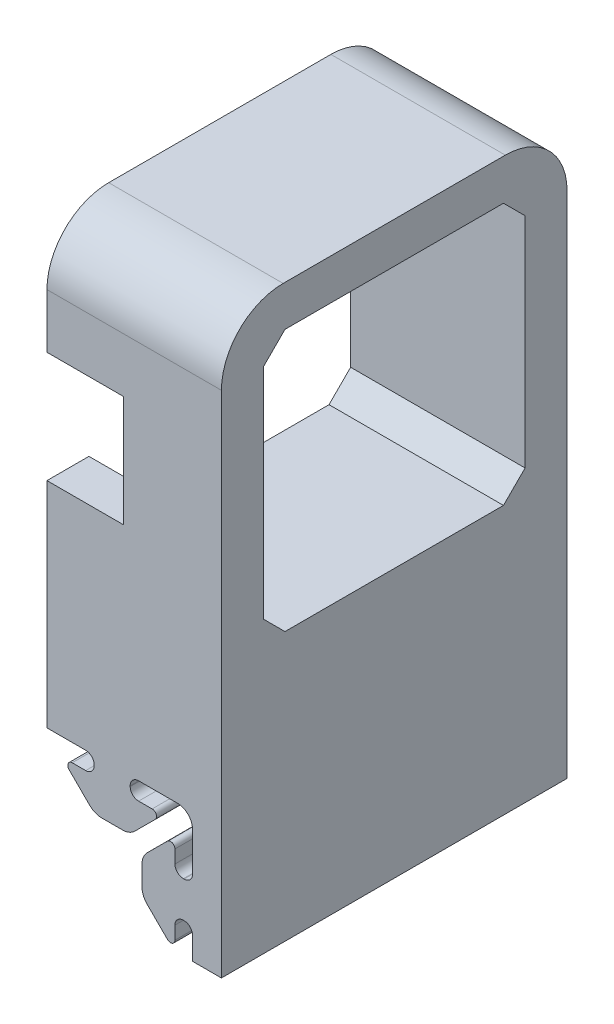
SolidWorks part; units mm, degrees
ref_plane "Front Plane" through (0, 0, 0) normal (0, 0, 1) x (1, 0, 0)
ref_plane "Top Plane" through (0, 0, 0) normal (0, 1, 0) x (1, 0, 0)
ref_plane "Right Plane" through (0, 0, 0) normal (1, 0, 0) x (0, 0, -1)
sketch "Sketch1" plane through (0, 0, 0) normal (0, 0, 1) x (1, 0, 0)
  line L0 (13.02, -7.9417) -> (17.7, -7.9417)
  line L1 (-10.5664, 13.02) -> (-10.5664, 84.52)
  line L2 (-10.5664, 84.52) -> (17.7, 84.52)
  line L3 (17.7, -7.9417) -> (17.7, 84.52)
  line L10 (12.7, -6.3331) -> (12.7, -7.9417) construction
  line L11 (13.02, -5.3171) -> (13.02, -4.2875)
  line L12 (11.651, -2.9185) -> (11.5392, -2.9185)
  line L13 (10.1702, -4.2875) -> (10.1702, -6.4021)
  line L14 (8.9631, -6.9029) -> (5.667, -3.6143)
  line L15 (4.8285, -1.5932) -> (4.8285, 1.5932)
  line L16 (5.667, 3.6143) -> (8.9631, 6.9029)
  line L17 (10.1702, 6.4021) -> (10.1702, 4.2875)
  line L18 (11.5392, 2.9185) -> (11.651, 2.9185)
  line L19 (13.02, 10.5773) -> (13.02, 4.2875)
  line L20 (6.3329, 13.02) -> (10.5626, 13.0198)
  line L22 (6.3329, 13.02) -> (4.2875, 13.02)
  line L23 (2.9185, 11.651) -> (2.9185, 11.5392)
  line L24 (4.2875, 10.1702) -> (6.4768, 10.1702)
  line L25 (6.981, 8.9509) -> (3.6723, 5.6497)
  line L26 (1.6558, 4.8158) -> (-1.6558, 4.8158)
  line L27 (-3.6723, 5.6497) -> (-6.981, 8.9509)
  line L28 (-6.4768, 10.1702) -> (-4.2875, 10.1702)
  line L29 (-2.9185, 11.5392) -> (-2.9185, 11.651)
  line L30 (-4.2875, 13.02) -> (-5.3171, 13.02)
  line L31 (-5.3171, 13.02) -> (-10.5664, 13.02)
  line L32 (13.02, -5.3171) -> (13.02, -7.9417)
  line L33 (13.02, -6.3331) -> (13.02, -7.9417) construction
  line L34 (13.02, 4.2875) -> (13.02, 5.3171) construction
  line L37 (5.3171, 13.02) -> (4.2875, 13.02) construction
  line L38 (-6.3331, 13.02) -> (-9.5504, 13.02) construction
  line L96 (12.7, -5.3171) -> (12.7, -4.2875) construction
  line L97 (11.651, -3.2385) -> (11.5392, -3.2385) construction
  line L98 (10.4902, -4.2875) -> (10.4902, -6.4021) construction
  line L99 (8.7371, -7.1294) -> (5.441, -3.8408) construction
  line L100 (4.5085, -1.5932) -> (4.5085, 1.5932) construction
  line L101 (5.441, 3.8408) -> (8.7371, 7.1294) construction
  line L102 (10.4902, 6.4021) -> (10.4902, 4.2875) construction
  line L103 (11.5392, 3.2385) -> (11.651, 3.2385) construction
  line L104 (12.7, 4.2875) -> (12.7, 5.3171) construction
  line L105 (12.7, 6.3331) -> (12.7, 9.5504) construction
  line L106 (9.5504, 12.7) -> (6.3331, 12.7) construction
  line L107 (5.3171, 12.7) -> (4.2875, 12.7) construction
  line L108 (3.2385, 11.651) -> (3.2385, 11.5392) construction
  line L109 (4.2875, 10.4902) -> (6.4768, 10.4902) construction
  line L110 (7.207, 8.7244) -> (3.8983, 5.4232) construction
  line L111 (1.6558, 4.4958) -> (-1.6558, 4.4958) construction
  line L112 (-3.8983, 5.4232) -> (-7.207, 8.7244) construction
  line L113 (-6.4768, 10.4902) -> (-4.2875, 10.4902) construction
  line L114 (-3.2385, 11.5392) -> (-3.2385, 11.651) construction
  line L115 (-4.2875, 12.7) -> (-5.3171, 12.7) construction
  line L116 (-6.3331, 12.7) -> (-9.5504, 12.7) construction
  arc A0 (13.02, -4.2875) -> (11.651, -2.9185) centre (11.651, -4.2875) ccw
  arc A1 (11.5392, -2.9185) -> (10.1702, -4.2875) centre (11.5392, -4.2875) ccw
  arc A2 (8.9631, -6.9029) -> (10.1702, -6.4021) centre (9.4628, -6.4021) ccw
  arc A3 (4.8285, -1.5932) -> (5.667, -3.6143) centre (7.6835, -1.5932) ccw
  arc A4 (5.667, 3.6143) -> (4.8285, 1.5932) centre (7.6835, 1.5932) ccw
  arc A5 (10.1702, 6.4021) -> (8.9631, 6.9029) centre (9.4628, 6.4021) ccw
  arc A6 (10.1702, 4.2875) -> (11.5392, 2.9185) centre (11.5392, 4.2875) ccw
  arc A7 (11.651, 2.9185) -> (13.02, 4.2875) centre (11.651, 4.2875) ccw
  arc A8 (4.2875, 13.02) -> (2.9185, 11.651) centre (4.2875, 11.651) ccw
  arc A9 (2.9185, 11.5392) -> (4.2875, 10.1702) centre (4.2875, 11.5392) ccw
  arc A10 (6.981, 8.9509) -> (6.4768, 10.1702) centre (6.4768, 9.4563) ccw
  arc A11 (1.6558, 4.8158) -> (3.6723, 5.6497) centre (1.6558, 7.6708) ccw
  arc A12 (-3.6723, 5.6497) -> (-1.6558, 4.8158) centre (-1.6558, 7.6708) ccw
  arc A13 (-6.4768, 10.1702) -> (-6.981, 8.9509) centre (-6.4768, 9.4563) ccw
  arc A14 (-4.2875, 10.1702) -> (-2.9185, 11.5392) centre (-4.2875, 11.5392) ccw
  arc A15 (-2.9185, 11.651) -> (-4.2875, 13.02) centre (-4.2875, 11.651) ccw
  arc A16 (13.02, 10.5773) -> (10.5626, 13.0198) centre (10.5918, 10.5918) ccw
  arc A17 (13.0198, 10.5625) -> (10.5626, 13.0198) centre (10.5918, 10.5918) ccw construction
  arc A114 (12.7, -5.3171) -> (12.7, -6.3331) centre (12.7, -5.8251) ccw construction
  arc A115 (12.7, -4.2875) -> (11.651, -3.2385) centre (11.651, -4.2875) ccw construction
  arc A116 (11.5392, -3.2385) -> (10.4902, -4.2875) centre (11.5392, -4.2875) ccw construction
  arc A117 (8.7371, -7.1294) -> (10.4902, -6.4021) centre (9.4628, -6.4021) ccw construction
  arc A118 (4.5085, -1.5932) -> (5.441, -3.8408) centre (7.6835, -1.5932) ccw construction
  arc A119 (5.441, 3.8408) -> (4.5085, 1.5932) centre (7.6835, 1.5932) ccw construction
  arc A120 (10.4902, 6.4021) -> (8.7371, 7.1294) centre (9.4628, 6.4021) ccw construction
  arc A121 (10.4902, 4.2875) -> (11.5392, 3.2385) centre (11.5392, 4.2875) ccw construction
  arc A122 (11.651, 3.2385) -> (12.7, 4.2875) centre (11.651, 4.2875) ccw construction
  arc A123 (12.7, 6.3331) -> (12.7, 5.3171) centre (12.7, 5.8251) ccw construction
  arc A124 (12.6998, 10.5664) -> (12.7, 9.5504) centre (12.7, 10.0584) ccw construction
  arc A125 (12.6998, 10.5664) -> (10.5664, 12.6998) centre (10.5918, 10.5918) ccw construction
  arc A126 (9.5504, 12.7) -> (10.5664, 12.6998) centre (10.0584, 12.7) ccw construction
  arc A127 (5.3171, 12.7) -> (6.3331, 12.7) centre (5.8251, 12.7) ccw construction
  arc A128 (4.2875, 12.7) -> (3.2385, 11.651) centre (4.2875, 11.651) ccw construction
  arc A129 (3.2385, 11.5392) -> (4.2875, 10.4902) centre (4.2875, 11.5392) ccw construction
  arc A130 (7.207, 8.7244) -> (6.4768, 10.4902) centre (6.4768, 9.4563) ccw construction
  arc A131 (1.6558, 4.4958) -> (3.8983, 5.4232) centre (1.6558, 7.6708) ccw construction
  arc A132 (-3.8983, 5.4232) -> (-1.6558, 4.4958) centre (-1.6558, 7.6708) ccw construction
  arc A133 (-6.4768, 10.4902) -> (-7.207, 8.7244) centre (-6.4768, 9.4563) ccw construction
  arc A134 (-4.2875, 10.4902) -> (-3.2385, 11.5392) centre (-4.2875, 11.5392) ccw construction
  arc A135 (-3.2385, 11.651) -> (-4.2875, 12.7) centre (-4.2875, 11.651) ccw construction
  arc A136 (-6.3331, 12.7) -> (-5.3171, 12.7) centre (-5.8251, 12.7) ccw construction
  arc A137 (-10.5664, 12.6998) -> (-9.5504, 12.7) centre (-10.0584, 12.7) ccw construction
  dimension "D1" = 71.5
  dimension "D6" = 5
  dimension "D8" = 0.32
  dimension "D7" = 6.2898
  dimension "D9" = 4.2297
extrude "Boss-Extrude1" add sketch "Sketch1" along normal blind 56 contours L3 L2 L1 L31 L30 A15 L29 A14 L28 A13 L27 A12 L26 A11 L25 A10 L24 A9 L23 A8 L22 L20 A16 L19 A7 L18 A6 L17 A5 L16 A4 L15 A3 L14 A2 L13 A1 L12 A0 L11 L32 L0
sketch "Sketch14" plane through (17.7, 0, 0) normal (1, 0, 0) x (0, 0, -1)
  line L4 (-56, -7.9417) -> (-56, 84.52) construction
  line L5 (0, -7.9417) -> (0, 84.52) construction
  line L6 (-56, 84.52) -> (0, 84.52) construction
  line L11 (0, 35.52) -> (-56, 35.52) construction
  line L12 (-28, 84.52) -> (-28, 35.52) construction
  line L14 (-49.2, 35.52) -> (-6.8, 35.52)
  line L15 (-49.2, 35.52) -> (-49.2, 77.92)
  line L16 (-49.2, 77.92) -> (-6.8, 77.92)
  line L17 (-6.8, 35.52) -> (-6.8, 77.92)
  point P14 (-28, 77.92)
  dimension "D1" = 42.4
  dimension "D2" = 42.4
  dimension "D3" = 6.6
other "AlignGroup1"
extrude "Cut-Extrude1" cut sketch "Sketch14" against normal blind 56
chamfer "Chamfer1" distance 3.5 4 edges at (3.5668, 35.52, 6.8) (3.5668, 35.52, 49.2) (3.5668, 77.92, 6.8) (3.5668, 77.92, 49.2)
fillet "Fillet1" radius 10 2 edges at (3.5668, 84.52, 56) (3.5668, 84.52, 0)
sketch "Sketch16" plane through (17.7, 0, 0) normal (1, 0, 0) x (0, 0, -1)
  line L1 (-56, -7.9417) -> (-43.6, -7.9417)
  line L2 (-56, -7.9417) -> (-56, 15.0583)
  line L3 (-56, 15.0583) -> (-43.6, 15.0583)
  line L4 (-43.6, -7.9417) -> (-43.6, 15.0583)
  dimension "D1" = 23
  dimension "D2" = 12.4
extrude "Cut-Extrude3" [suppressed] cut sketch "Sketch16" against normal through all
sketch "Sketch17" plane through (0, 0, 56) normal (0, 0, 1) x (1, 0, 0)
  line L0 (17.7, 56.72) -> (-10.5664, 56.72) construction
  line L2 (-13.62, 65.72) -> (1.8336, 65.72)
  line L3 (-13.62, 65.72) -> (-13.62, 47.72)
  line L4 (17.7, 39.02) -> (17.7, 74.42)
  line L5 (-10.5664, 39.02) -> (17.7, 39.02)
  line L6 (-10.5664, 74.42) -> (-10.5664, 39.02)
  line L7 (17.7, 74.42) -> (-10.5664, 74.42)
  line L8 (17.7, 39.02) -> (17.7, 74.42) construction
  line L9 (-10.5664, 39.02) -> (17.7, 39.02) construction
  line L10 (-10.5664, 74.42) -> (-10.5664, 39.02) construction
  line L12 (-13.62, 47.72) -> (1.8336, 47.72)
  line L13 (1.8336, 65.72) -> (1.8336, 47.72)
  point P10 (1.8336, 56.72)
  dimension "D2" = 18
  dimension "D3" = 12.4
  dimension "D1" = 0
extrude "Cut-Extrude4" cut sketch "Sketch17" against normal up to next
fillet "Fillet4" [suppressed] radius 15
sketch "Sketch18" plane through (0, 0, 0) normal (0, 0, -1) x (-1, 0, 0)
  line L0 (-23.6085, 16.9143) -> (-37.3681, 16.9143)
  line L1 (-23.6085, 72.8358) -> (16.3915, 72.8358)
  line L2 (-23.6085, 72.8358) -> (-23.6085, 16.9143)
  line L3 (-23.6085, -12.2016) -> (16.3915, -12.2016)
  line L4 (16.3915, 72.8358) -> (16.3915, -12.2016)
  line L5 (-37.3681, 16.9143) -> (-37.3681, -12.2016)
  line L6 (-37.3681, -12.2016) -> (-23.6085, -12.2016)
  dimension "D1" = 85.0374
  dimension "D2" = 40
